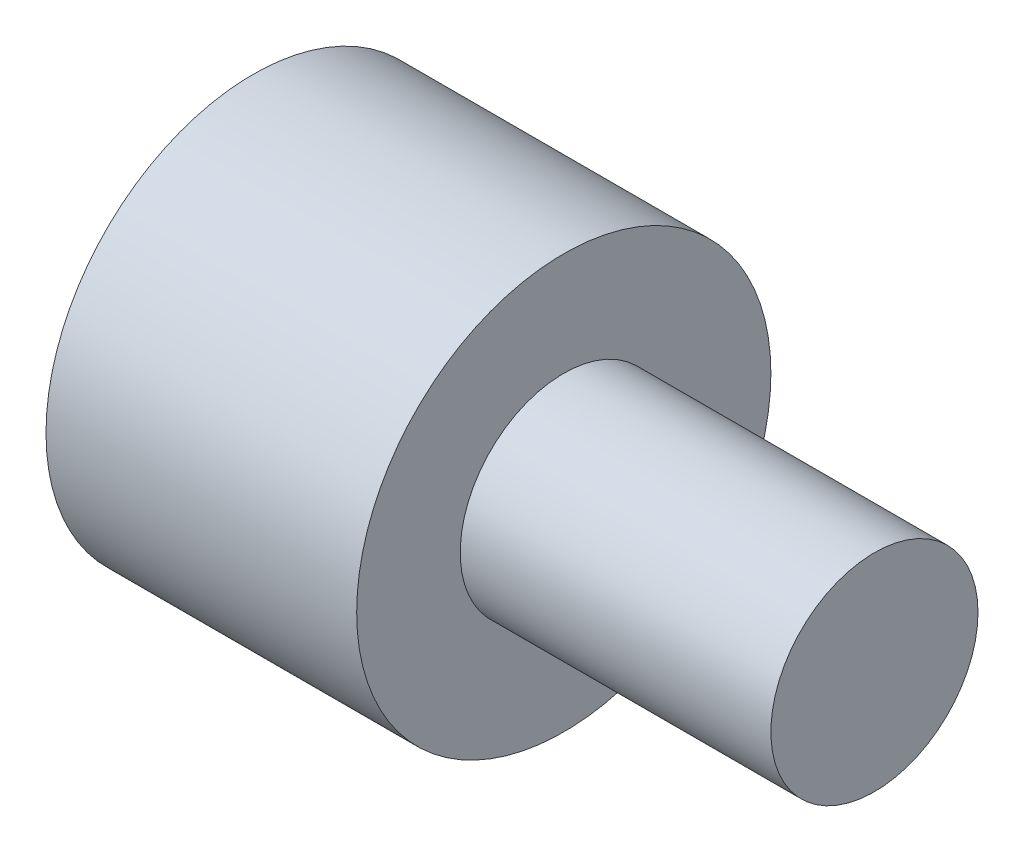
SolidWorks part; units mm, degrees
ref_plane "Front Plane" through (0, 0, 0) normal (0, 0, 1) x (1, 0, 0)
ref_plane "Top Plane" through (0, 0, 0) normal (0, 1, 0) x (1, 0, 0)
ref_plane "Right Plane" through (0, 0, 0) normal (1, 0, 0) x (0, 0, -1)
sketch "Sketch1" plane through (0, 0, 0) normal (1, 0, 0) x (0, 0, -1)
  circle A0 centre (0, 0) radius 20
  dimension "D1" = 40
extrude "Boss-Extrude1" add sketch "Sketch1" along normal blind 30
sketch "Sketch2" plane through (30, 0, 0) normal (1, 0, 0) x (0, 0, -1)
  circle A0 centre (0, 0) radius 10
  dimension "D1" = 20
extrude "Boss-Extrude2" add sketch "Sketch2" along normal blind 30
